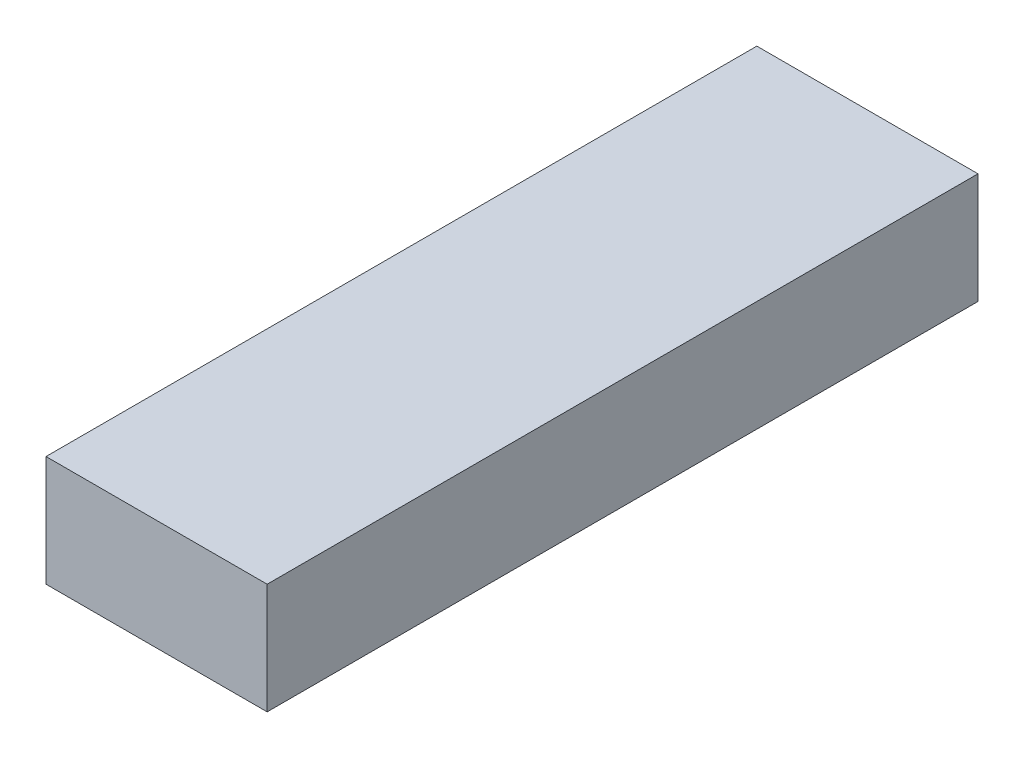
SolidWorks part; units mm, degrees
ref_plane "Front Plane" through (0, 0, 0) normal (0, 0, 1) x (1, 0, 0)
ref_plane "Top Plane" through (0, 0, 0) normal (0, 1, 0) x (1, 0, 0)
ref_plane "Right Plane" through (0, 0, 0) normal (1, 0, 0) x (0, 0, -1)
sketch "Sketch1" plane through (0, 0, 0) normal (0, 0, 1) x (1, 0, 0)
  line L1 (0, 0) -> (14, 0)
  line L2 (0, 0) -> (0, 7)
  line L3 (0, 7) -> (14, 7)
  line L4 (14, 0) -> (14, 7)
  dimension "D1" = 7
  dimension "D2" = 14
extrude "Boss-Extrude1" add sketch "Sketch1" along normal blind 45
